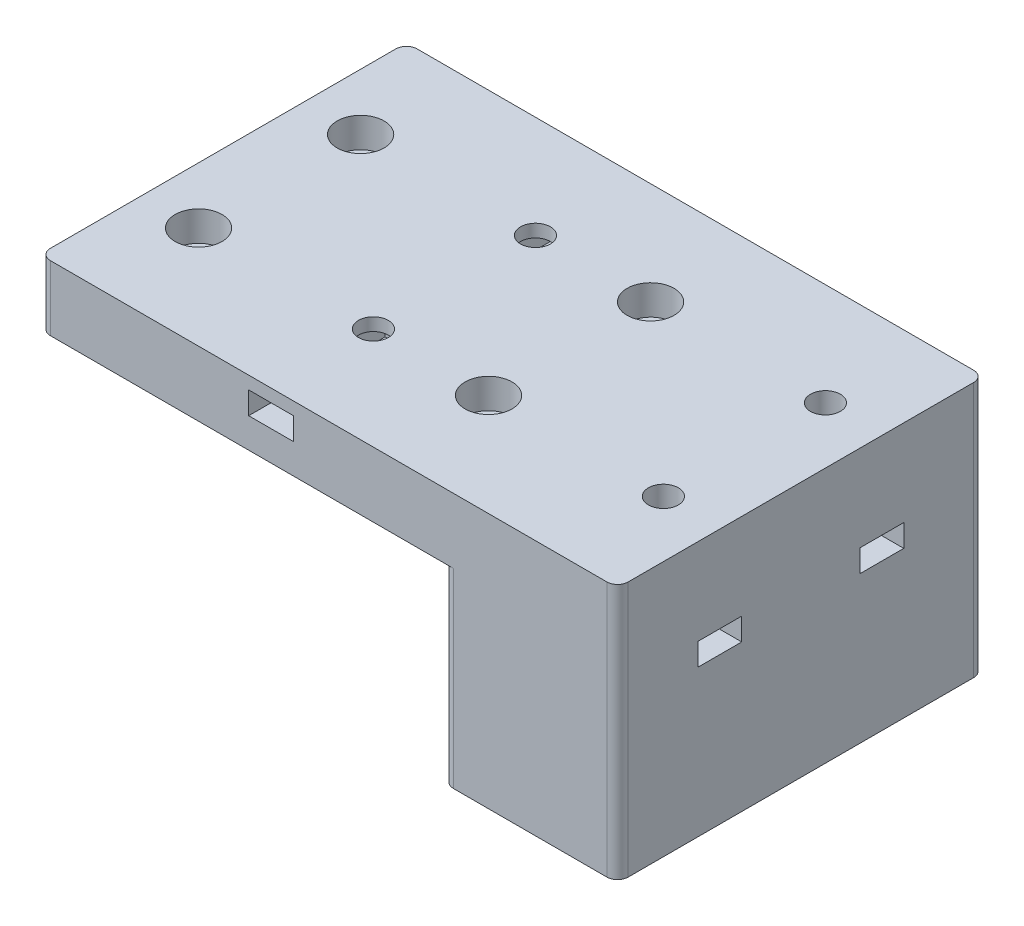
SolidWorks part; units mm, degrees
ref_plane "Front Plane" through (0, 0, 0) normal (0, 0, 1) x (1, 0, 0)
ref_plane "Top Plane" through (0, 0, 0) normal (0, 1, 0) x (1, 0, 0)
ref_plane "Right Plane" through (0, 0, 0) normal (1, 0, 0) x (0, 0, -1)
sketch "Sketch1" plane through (0, 0, 0) normal (0, 0, 1) x (1, 0, 0)
  line L0 (0, 0) -> (0, -44.7)
  line L1 (0, -44.7) -> (41, -44.7)
  line L2 (41, -44.7) -> (41, 15.25)
  line L3 (41, 15.25) -> (-94.5, 15.25)
  line L4 (-94.5, 15.25) -> (-94.5, 0)
  line L5 (-94.5, 0) -> (0, 0)
  dimension "D1" = 94.5
  dimension "D2" = 41
  dimension "D3" = 15.25
  dimension "D4" = 44.7
extrude "Boss-Extrude1" add sketch "Sketch1" along normal mid plane 86
sketch "Sketch2" plane through (0, 15.25, 0) normal (0, 1, 0) x (1, 0, 0)
  line L0 (-47.25, 43) -> (-47.25, -43) construction
  line L2 (41, 43) -> (-94.5, 43) construction
  line L5 (41, -43) -> (41, 43) construction
  line L7 (41, -43) -> (-94.5, -43) construction
  line L8 (-94.5, -43) -> (0, -43) construction
  point P0 (-81.25, 19)
  point P1 (-81.25, -19)
  point P2 (-13.25, -19)
  point P3 (-13.25, 19)
  point P13 (-47.25, 0)
  point P18 (27.75, 19)
  point P20 (27.75, -19)
  point P31 (-40.25, 19)
  point P33 (-40.25, -19)
  point P58 (-47.25, -43)
  dimension "D1" = 34
  dimension "D2" = 19
  dimension "D3" = 19
  dimension "D4" = 13.25
  dimension "D5" = 68
hole_wizard "M6 Clearance Hole1" positions "Sketch2" profile "Sketch3" hole size "M6" standard "ISO"
sketch "Sketch3" plane through (-81.25, 15.25, -19) normal (1, 0, 0) x (0, 0, 1)
  line L0 (0, 0) -> (0, 15.25)
  line L1 (0, 15.25) -> (3.5, 15.25)
  line L2 (3.5, 15.25) -> (3.5, 0)
  line L5 (3.5, 0) -> (0, 0)
  line L11 (0, -6.35) -> (0, 107.95) construction
  dimension "Thru Hole Dia." = 7
  dimension "Thru Hole Depth" = 15.25
sketch "Sketch4" plane through (0, 15.25, 0) normal (0, 1, 0) x (1, 0, 0)
  circle A0 centre (-81.25, 19) radius 5.5
  circle A1 centre (-81.25, -19) radius 5.5
  circle A2 centre (-13.25, 19) radius 5.5
  circle A3 centre (-13.25, -19) radius 5.5
  dimension "D1" = 11
extrude "Cut-Extrude1" cut sketch "Sketch4" against normal blind 7
sketch "Sketch5" plane through (41, 0, 0) normal (1, 0, 0) x (0, 0, -1)
  line L1 (-24.125, -5) -> (-13.875, -5)
  line L2 (-24.125, -5) -> (-24.125, -10.25)
  line L3 (-24.125, -10.25) -> (-13.875, -10.25)
  line L4 (-13.875, -5) -> (-13.875, -10.25)
  line L5 (13.875, -5) -> (24.125, -5)
  line L6 (13.875, -5) -> (13.875, -10.25)
  line L7 (13.875, -10.25) -> (24.125, -10.25)
  line L8 (24.125, -5) -> (24.125, -10.25)
  line L9 (0, 15.25) -> (0, -44.7) construction
  line L10 (-43, 15.25) -> (43, 15.25) construction
  line L11 (-43, -44.7) -> (43, -44.7) construction
  line L12 (-43, 0) -> (43, 0) construction
  point P8 (-19, -10.25)
  point P10 (19, -10.25)
  dimension "D1" = 5.25
  dimension "D2" = 10.25
  dimension "D3" = 19
  dimension "D4" = 19
  dimension "D5" = 5
extrude "Cut-Extrude2" cut sketch "Sketch5" against normal blind 22
sketch "Sketch6" plane through (0, 0, 43) normal (0, 0, 1) x (1, 0, 0)
  line L0 (41, 15.25) -> (-94.5, 15.25) construction
  line L1 (-45.5, 12.25) -> (-35, 12.25)
  line L2 (-45.5, 12.25) -> (-45.5, 7)
  line L3 (-45.5, 7) -> (-35, 7)
  line L4 (-35, 12.25) -> (-35, 7)
  line L5 (-40.25, 7) -> (-40.25, 12.25) construction
  line L6 (-45.5, 9.625) -> (-35, 9.625) construction
  line L7 (41, -44.7) -> (41, 15.25) construction
  point P0 (-40.25, 9.625)
  dimension "D1" = 5.25
  dimension "D2" = 10.5
  dimension "D3" = 3
  dimension "D4" = 81.25
extrude "Cut-Extrude3" cut sketch "Sketch6" against normal blind 32
mirror "Mirror1" about plane through (0, 0, 0) normal (0, 0, 1) of "Cut-Extrude3"
fillet "Fillet1" radius 2.5 6 edges at (41, -14.725, -43) (41, -14.725, 43) (-94.5, 7.625, -43) (-94.5, 7.625, 43) (0, -22.35, -43) (0, -22.35, 43)
